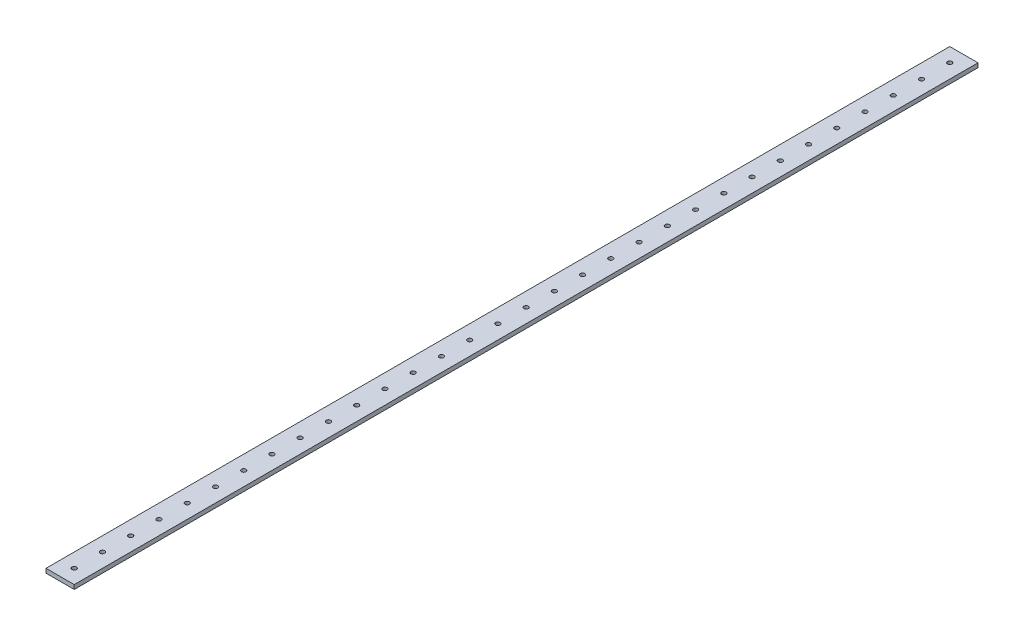
SolidWorks part; units mm, degrees
ref_plane "前视基准面" through (0, 0, 0) normal (0, 0, 1) x (1, 0, 0)
ref_plane "上视基准面" through (0, 0, 0) normal (0, 1, 0) x (1, 0, 0)
ref_plane "右视基准面" through (0, 0, 0) normal (1, 0, 0) x (0, 0, -1)
other "Configuration Table"
sketch "草图1" plane through (0, 0, 0) normal (0, 0, 1) x (1, 0, 0)
  line L1 (0, 0) -> (20, 0)
  line L2 (0, 0) -> (0, -3)
  line L3 (0, -3) -> (20, -3)
  line L4 (20, 0) -> (20, -3)
  dimension "D1" = 20
  dimension "D2" = 3
extrude "凸台-拉伸1" add sketch "草图1" along normal blind 640
sketch "草图2" plane through (0, 0, 0) normal (0, 1, 0) x (1, 0, 0)
  line L1 (20, 0) -> (0, 0) construction
  line L2 (10, 0) -> (10, -10) construction
  circle A0 centre (10, -10) radius 1.575
  circle A1 centre (10, -30) radius 1.575
  circle A2 centre (10, -50) radius 1.575
  circle A3 centre (10, -70) radius 1.575
  circle A4 centre (10, -90) radius 1.575
  circle A5 centre (10, -110) radius 1.575
  circle A6 centre (10, -130) radius 1.575
  circle A7 centre (10, -150) radius 1.575
  circle A8 centre (10, -170) radius 1.575
  circle A9 centre (10, -190) radius 1.575
  circle A10 centre (10, -210) radius 1.575
  circle A11 centre (10, -230) radius 1.575
  circle A12 centre (10, -250) radius 1.575
  circle A13 centre (10, -270) radius 1.575
  circle A14 centre (10, -290) radius 1.575
  circle A15 centre (10, -310) radius 1.575
  circle A16 centre (10, -330) radius 1.575
  circle A17 centre (10, -350) radius 1.575
  circle A18 centre (10, -370) radius 1.575
  circle A19 centre (10, -390) radius 1.575
  circle A20 centre (10, -410) radius 1.575
  circle A21 centre (10, -430) radius 1.575
  circle A22 centre (10, -450) radius 1.575
  circle A23 centre (10, -470) radius 1.575
  circle A24 centre (10, -490) radius 1.575
  circle A25 centre (10, -510) radius 1.575
  circle A26 centre (10, -530) radius 1.575
  circle A27 centre (10, -550) radius 1.575
  circle A28 centre (10, -570) radius 1.575
  circle A29 centre (10, -590) radius 1.575
  circle A30 centre (10, -610) radius 1.575
  circle A31 centre (10, -630) radius 1.575
  circle A33 centre (10, -650) radius 1.575 [skipped]
  dimension "D1" = 3.15
  dimension "D2" = 33
  dimension "D3" = 10
  dimension "D4" = 20
extrude "切除-拉伸1" cut sketch "草图2" against normal through all
